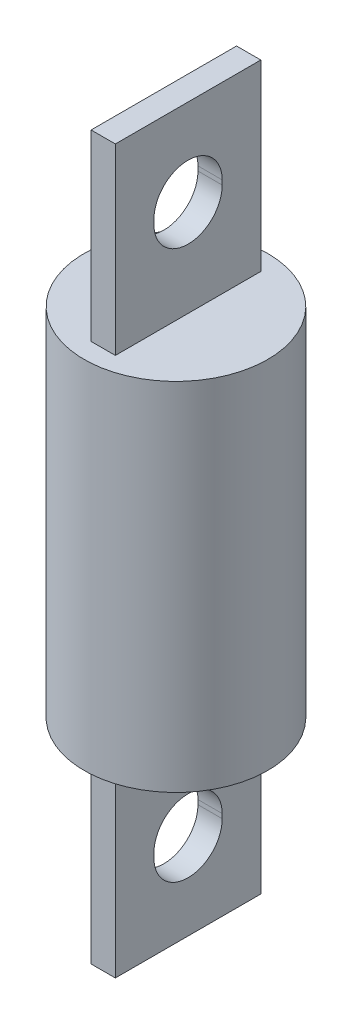
SolidWorks part; units mm, degrees
ref_plane "Front Plane" through (0, 0, 0) normal (0, 0, 1) x (1, 0, 0)
ref_plane "Top Plane" through (0, 0, 0) normal (0, 1, 0) x (1, 0, 0)
ref_plane "Right Plane" through (0, 0, 0) normal (1, 0, 0) x (0, 0, -1)
sketch "Sketch1" plane through (0, 0, 0) normal (0, 1, 0) x (1, 0, 0)
  circle A0 centre (0, 0) radius 12.0269
  dimension "D1" = 24.0538
extrude "Boss-Extrude1" add sketch "Sketch1" along normal mid plane 46.6344
sketch "Sketch3" plane through (0, 23.3172, 0) normal (0, 1, 0) x (1, 0, 0)
  line L1 (1.5875, 9.525) -> (-1.5875, 9.525)
  line L2 (1.5875, 9.525) -> (1.5875, -9.525)
  line L3 (1.5875, -9.525) -> (-1.5875, -9.525)
  line L4 (-1.5875, 9.525) -> (-1.5875, -9.525)
  line L5 (1.5875, 9.525) -> (-1.5875, -9.525) construction
  line L6 (1.5875, -9.525) -> (-1.5875, 9.525) construction
  point P0 (0, 0)
  dimension "D1" = 3.175
  dimension "D2" = 19.05
extrude "Boss-Extrude3" add sketch "Sketch3" along normal blind 23.9903
sketch "Sketch4" plane through (1.5875, 0, 0) normal (1, 0, 0) x (0, 0, -1)
  line L0 (0, 36.2331) -> (0, 35.6489) construction
  line L1 (4.4704, 36.2331) -> (4.4704, 35.6489)
  line L2 (-4.4704, 36.2331) -> (-4.4704, 35.6489)
  line L3 (0, 0) -> (31.8538, 0) construction
  line L4 (0, -36.2331) -> (0, -35.6489) construction
  line L5 (4.4704, -36.2331) -> (4.4704, -35.6489)
  line L6 (-4.4704, -36.2331) -> (-4.4704, -35.6489)
  arc A0 (4.4704, 36.2331) -> (-4.4704, 36.2331) centre (0, 36.2331) ccw
  arc A1 (-4.4704, 35.6489) -> (4.4704, 35.6489) centre (0, 35.6489) ccw
  arc A2 (4.4704, -36.2331) -> (-4.4704, -36.2331) centre (0, -36.2331) cw
  arc A3 (-4.4704, -35.6489) -> (4.4704, -35.6489) centre (0, -35.6489) cw
  point P3 (0, 35.941)
  point P14 (0, -35.941)
  dimension "D1" = 4.4704
  dimension "D2" = 36.2331
  dimension "D3" = 35.6489
extrude "Cut-Extrude1" cut sketch "Sketch4" against normal blind 10
mirror "Mirror1" about plane through (0, 0, 0) normal (0, 1, 0) of "Cut-Extrude1", "Boss-Extrude3"
sketch "Sketch7" [suppressed] plane through (0, 0, 0) normal (1, 0, 0) x (0, 0, -1)
  text T0 "35-200 Amps" font "Century Gothic" height in points 8
sketch "Sketch8" [suppressed] plane through (0, 46.0375, 0) normal (0, 1, 0) x (1, 0, 0)
  text T0 "200 Amps" font "Century Gothic" height in points 8
